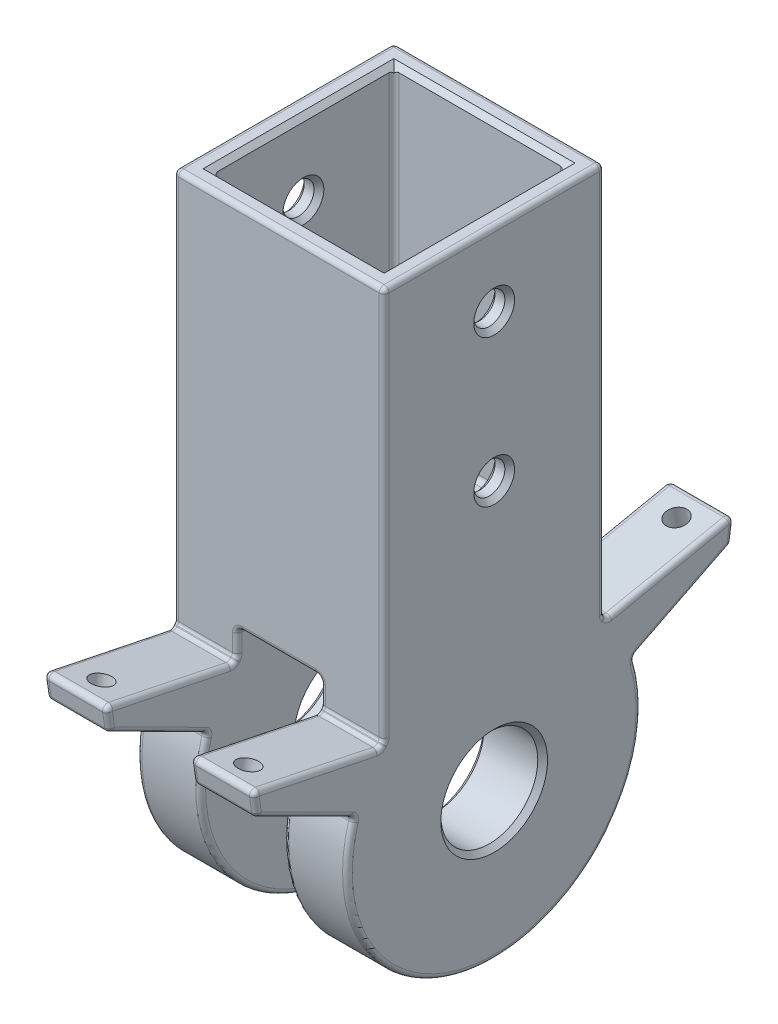
SolidWorks part; units mm, degrees
ref_plane "Front Plane" through (0, 0, 0) normal (0, 0, 1) x (1, 0, 0)
ref_plane "Top Plane" through (0, 0, 0) normal (0, 1, 0) x (1, 0, 0)
ref_plane "Right Plane" through (0, 0, 0) normal (1, 0, 0) x (0, 0, -1)
sketch "Sketch1" plane through (0, 0, 0) normal (1, 0, 0) x (0, 0, -1)
  line L0 (0, 9.906) -> (0, -30) construction
  line L1 (23.2287, 18.985) -> (49.2287, 24.3425)
  line L3 (-22.5, 19.8431) -> (-22.5, 99.8431)
  line L4 (-22.5, 99.8431) -> (22.5, 99.8431)
  line L5 (22.5, 19.8431) -> (22.5, 99.8431)
  line L6 (49.2287, 24.3425) -> (48.502, 19.3956)
  line L7 (48.502, 19.3956) -> (28.502, 9.3614)
  line L8 (-48.502, 19.3956) -> (-28.502, 9.3614)
  line L9 (-49.2287, 24.3425) -> (-48.502, 19.3956)
  line L10 (-23.2287, 18.985) -> (-49.2287, 24.3425)
  arc A0 (-22.5, 19.8431) -> (-23.2287, 18.985) centre (0, 0) ccw
  circle A1 centre (0, 0) radius 9.906
  arc A2 (23.2287, 18.985) -> (22.5, 19.8431) centre (0, 0) ccw
  arc A3 (-28.502, 9.3614) -> (28.502, 9.3614) centre (0, 0) ccw
  point P6 (-22.5, 19.8431)
  point P7 (22.5, 19.8431)
  dimension "D1" = 19.812
  dimension "D2" = 60
  dimension "D3" = 80
  dimension "D4" = 45
  dimension "D5" = 26
  dimension "D6" = 20
  dimension "D7" = 5
  dimension "D8" = 235
  dimension "D9" = 290
  dimension "D10" = 10.9736
extrude "Boss-Extrude1" add sketch "Sketch1" along normal blind 43
sketch "Sketch2" plane through (0, 0, 0) normal (0, 0, 1) x (1, 0, 0)
  line L0 (30, 99.8431) -> (30, -50.1569) construction
  line L1 (13, 99.8431) -> (13, -50.1569) construction
  line L2 (43, -60.1569) -> (0, -60.1569) construction
  line L3 (30, 19.8431) -> (43, 19.8431) construction
  line L4 (0, 99.8431) -> (0, 19.8431)
  line L5 (43, 99.8431) -> (0, 99.8431)
  line L6 (43, 19.8431) -> (43, 99.8431)
  line L7 (0, 19.8431) -> (43, 19.8431)
  line L8 (0, 99.8431) -> (0, -60.1569) construction
  line L9 (43, 99.8431) -> (0, 99.8431) construction
  line L10 (43, -60.1569) -> (43, 99.8431) construction
  line L12 (30, 24.8431) -> (13, 24.8431)
  line L13 (30, 24.8431) -> (30, -50.1569)
  line L14 (30, -50.1569) -> (13, -50.1569)
  line L15 (13, 24.8431) -> (13, -50.1569)
  line L19 (0, 19.8431) -> (13, 19.8431) construction
  point P10 (13, 24.8431)
  point P12 (30, 24.8431)
  dimension "D2" = 13
  dimension "D3" = 13
  dimension "D4" = 5
  dimension "D1" = 0
extrude "Cut-Extrude1" cut sketch "Sketch2" along normal blind 90 and the other way blind 90 contours L12 L15 L14 L13
sketch "Sketch3" plane through (30, 0, 0) normal (-1, 0, 0) x (0, 0, 1)
  circle A0 centre (0, 0) radius 30
  dimension "D1" = 60
extrude "Cut-Extrude2" cut sketch "Sketch3" along normal up to surface (17 mm away) up to face at (13, -9.906, 0)
sketch "Sketch4" plane through (43, 0, 0) normal (1, 0, 0) x (0, 0, -1)
  line L3 (22.5, 19.8431) -> (22.5, 99.8431)
  line L4 (22.5, 99.8431) -> (-22.5, 99.8431)
  line L5 (-22.5, 99.8431) -> (-22.5, 19.8431)
  line L6 (22.5, 19.8431) -> (22.5, 99.8431) construction
  line L7 (22.5, 99.8431) -> (-22.5, 99.8431) construction
  line L8 (-22.5, 99.8431) -> (-22.5, 19.8431) construction
  line L15 (-23.2287, 18.985) -> (-49.2287, 24.3425)
  line L16 (-23.2287, 18.985) -> (-49.2287, 24.3425)
  line L17 (-49.2287, 24.3425) -> (-48.502, 19.3956)
  line L18 (-49.2287, 24.3425) -> (-48.502, 19.3956)
  line L19 (-48.502, 19.3956) -> (-28.502, 9.3614)
  line L20 (-48.502, 19.3956) -> (-28.502, 9.3614)
  line L21 (28.502, 9.3614) -> (48.502, 19.3956)
  line L22 (28.502, 9.3614) -> (48.502, 19.3956)
  line L23 (48.502, 19.3956) -> (49.2287, 24.3425)
  line L24 (48.502, 19.3956) -> (49.2287, 24.3425)
  line L25 (49.2287, 24.3425) -> (23.2287, 18.985)
  line L26 (49.2287, 24.3425) -> (23.2287, 18.985)
  circle A0 centre (0, 54.8431) radius 3.175
  circle A3 centre (0, 84.8431) radius 3.175
  arc A4 (-22.5, 19.8431) -> (-23.2287, 18.985) centre (0, 0) ccw
  arc A5 (-22.5, 19.8431) -> (-23.2287, 18.985) centre (0, 0) ccw construction
  arc A8 (23.2287, 18.985) -> (22.5, 19.8431) centre (0, 0) ccw
  arc A9 (23.2287, 18.985) -> (22.5, 19.8431) centre (0, 0) ccw
  arc A10 (-28.502, 9.3614) -> (28.502, 9.3614) centre (0, 0) ccw
  arc A11 (-28.502, 9.3614) -> (28.502, 9.3614) centre (0, 0) ccw
  point P9 (0, 99.8431)
  dimension "D2" = 6.35
  dimension "D3" = 30
  dimension "D4" = 15
  dimension "D1" = 0
extrude "Cut-Extrude3" cut sketch "Sketch4" against normal through all contours A3 | A0
fillet "Fillet1" radius 1 78 edges at (43, 19.4175, -22.8684) (30, 19.4175, -22.8684) (0, 19.4175, -22.8684) (13, 19.4175, -22.8684) (13, 19.4175, 22.8684) (0, 19.4175, 22.8684) (43, 19.4175, 22.8684) (30, 19.4175, 22.8684) (0, 21.6637, 36.2287) (6.5, 18.985, 23.2287) (13, 21.6637, 36.2287) (36.5, 18.985, 23.2287) (43, 21.6637, 36.2287) (30, 21.6637, 36.2287) (36.5, 24.3425, 49.2287) (43, 21.869, 48.8653) (30, 21.869, 48.8653) (0, 21.869, 48.8653) (6.5, 24.3425, 49.2287) (13, 21.869, 48.8653) (43, 21.869, -48.8653) (30, 21.869, -48.8653) (0, 21.869, -48.8653) (13, 21.869, -48.8653) (13, 24.8431, 19.6586) (30, 24.8431, 19.6586) (30, 24.8431, -19.6586) (13, 24.8431, -19.6586) (13, 30, 0) (30, 30, 0) (21.5, 24.8431, 16.8172) (21.5, 24.8431, -16.8172) (43, 14.3785, -38.502) (36.5, 19.3956, -48.502) (30, 14.3785, -38.502) (36.5, 19.3956, 48.502) (43, 14.3785, 38.502) (30, 14.3785, 38.502) (0, 14.3785, 38.502) (6.5, 19.3956, 48.502) (13, 14.3785, 38.502) (0, 14.3785, -38.502) (13, 14.3785, -38.502) (6.5, 19.3956, -48.502) (0, -30, 0) (6.5, 9.3614, 28.502) (13, -30, 0) (6.5, 9.3614, -28.502) (36.5, 9.3614, 28.502) (43, -30, 0) (36.5, 9.3614, -28.502) (30, -30, 0) (0, 21.6637, -36.2287) (6.5, 24.3425, -49.2287) (13, 21.6637, -36.2287) (6.5, 18.985, -23.2287) (36.5, 24.3425, -49.2287) (43, 21.6637, -36.2287) (36.5, 18.985, -23.2287) (30, 21.6637, -36.2287) (36.5, 19.8431, -22.5) (43, 59.8431, -22.5) (0, 59.8431, -22.5) (6.5, 19.8431, -22.5) (13, 22.3431, -22.5) (21.5, 24.8431, -22.5) (30, 22.3431, -22.5) (21.5, 99.8431, -22.5) (43, 99.8431, 0) (0, 99.8431, 0) (21.5, 24.8431, 22.5) (13, 22.3431, 22.5) (6.5, 19.8431, 22.5) (0, 59.8431, 22.5) (21.5, 99.8431, 22.5) (43, 59.8431, 22.5) (36.5, 19.8431, 22.5) (30, 22.3431, 22.5)
chamfer "Chamfer1" distance 1 angle 45 8 edges at (0, 84.8431, -3.175) (0, 54.8431, -3.175) (43, 54.8431, -3.175) (43, 84.8431, -3.175) (30, -9.906, 0) (13, -9.906, 0) (0, 0, -9.906) (43, 0, -9.906)
sketch "Sketch6" plane through (0, 99.8431, 0) normal (0, 1, 0) x (1, 0, 0)
  line L16 (39, -18.5) -> (39, 18.5)
  line L17 (39, 18.5) -> (4, 18.5)
  line L18 (4, 18.5) -> (4, -18.5)
  line L19 (4, -18.5) -> (39, -18.5)
  line L20 (39, -18.5) -> (39, 18.5)
  line L21 (39, 18.5) -> (4, 18.5)
  line L22 (4, 18.5) -> (4, -18.5)
  line L23 (4, -18.5) -> (39, -18.5)
  dimension "D1" = 3
extrude "Cut-Extrude4" cut sketch "Sketch6" against normal blind 65
chamfer "Chamfer2" distance 1 angle 45 8 edges at (4, 84.8431, 3.175) (4, 54.8431, 3.175) (39, 84.8431, -3.175) (39, 54.8431, -3.175) (21.5, 99.8431, -18.5) (4, 99.8431, 0) (39, 99.8431, 0) (21.5, 99.8431, 18.5)
fillet "Fillet2" radius 1 8 edges at (4, 66.8431, 18.5) (4, 66.8431, -18.5) (39, 66.8431, -18.5) (21.5, 34.8431, -18.5) (4, 34.8431, 0) (39, 34.8431, 0) (21.5, 34.8431, 18.5) (39, 66.8431, 18.5)
sketch "Sketch8" plane through (0, 13.6202, 2.8066) normal (0, 0.9794, 0.2018) x (1, 0, 0)
  line L1 (42, 51.7003) -> (31, 51.7003) construction
  line L3 (36.5, 49.7003) -> (36.5, 51.7003) construction
  circle A0 centre (36.5, 47.5503) radius 2.15
  dimension "D1" = 4.3
  dimension "D2" = 2
extrude "Cut-Extrude6" cut sketch "Sketch8" against normal blind 15 contours A0
pattern_linear "LPattern1" count 2 spacing 30 along (-1, 0, 0) of "Cut-Extrude6"
mirror "Mirror1" about plane through (0, 0, 0) normal (0, 0, 1) of "LPattern1", "Cut-Extrude6"
